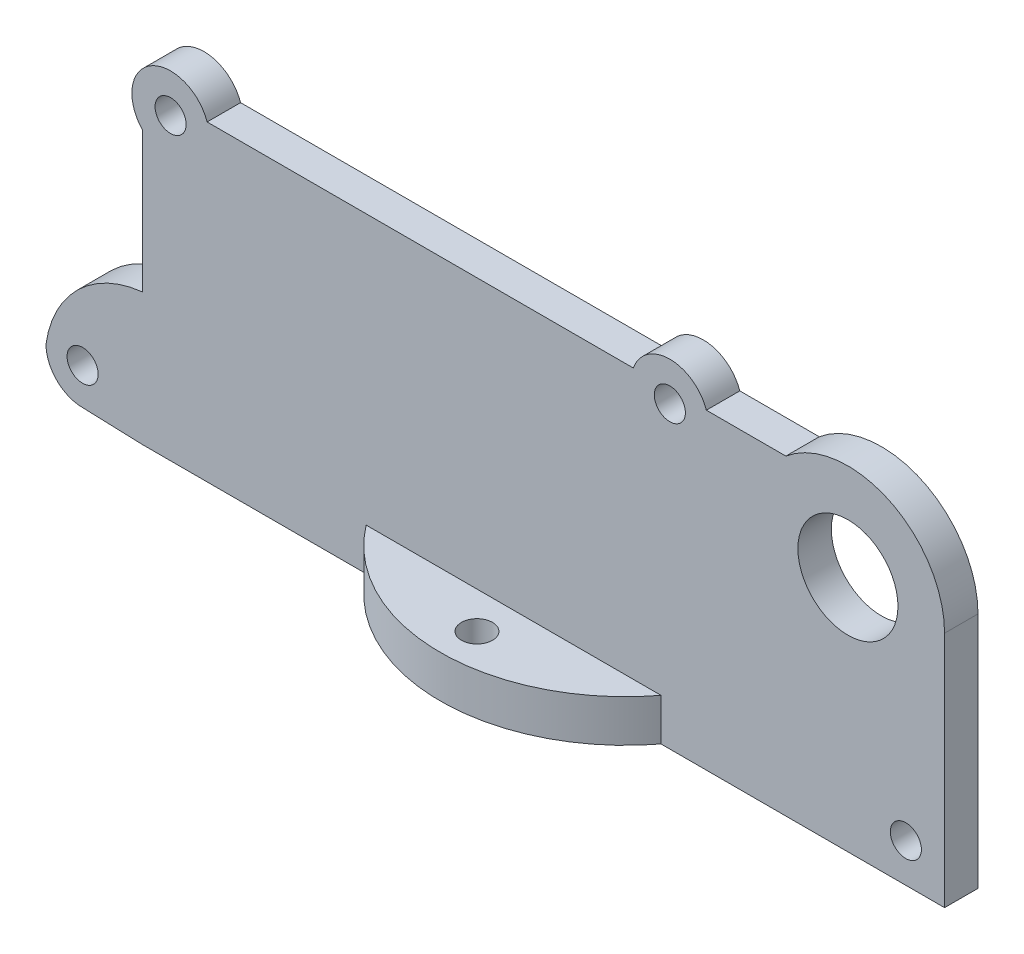
SolidWorks part; units mm, degrees
ref_plane "Front Plane" through (0, 0, 0) normal (0, 0, 1) x (1, 0, 0)
ref_plane "Top Plane" through (0, 0, 0) normal (0, 1, 0) x (1, 0, 0)
ref_plane "Right Plane" through (0, 0, 0) normal (1, 0, 0) x (0, 0, -1)
sketch "Sketch1" plane through (0, 0, 0) normal (0, 0, 1) x (1, 0, 0)
  line L1 (-26.416, -9.8) -> (26.416, -9.8)
  line L2 (-26.416, -9.8) -> (-26.416, 9.8)
  line L3 (-26.416, 9.8) -> (26.416, 9.8)
  line L4 (26.416, -9.8) -> (26.416, 9.8)
  line L5 (-26.416, -9.8) -> (26.416, 9.8) construction
  line L6 (-26.416, 9.8) -> (26.416, -9.8) construction
  line L7 (-20.15, -9.8) -> (20.15, -9.8)
  line L8 (-20.15, -9.8) -> (-20.15, 9.8)
  line L9 (-20.15, 9.8) -> (20.15, 9.8)
  line L10 (20.15, -9.8) -> (20.15, 9.8)
  line L11 (-20.15, -9.8) -> (20.15, 9.8) construction
  line L12 (-20.15, 9.8) -> (20.15, -9.8) construction
  line L13 (-26.416, 9.8) -> (26.416, 9.8)
  line L14 (-26.416, 9.8) -> (-26.416, 14.8)
  line L15 (-26.416, 14.8) -> (26.416, 14.8)
  line L16 (26.416, 9.8) -> (26.416, 14.8)
  line L17 (26.416, -9.8) -> (-26.416, -9.8)
  line L18 (26.416, -9.8) -> (26.416, -14.8)
  line L19 (26.416, -14.8) -> (-26.416, -14.8)
  line L20 (-26.416, -9.8) -> (-26.416, -14.8)
  circle A0 centre (-23.95, -4.974) radius 1.675
  circle A1 centre (-23.95, 4.974) radius 1.675
  circle A2 centre (23.95, 4.974) radius 1.675
  circle A3 centre (23.95, -4.974) radius 1.675
  point P0 (0, 0)
  point P14 (0, 0)
  dimension "D1" = 3.35
  dimension "D2" = 3.35
  dimension "D3" = 3.35
  dimension "D4" = 3.35
  dimension "D7" = 4.826
  dimension "D8" = 3.8
  dimension "D9" = 3.8
  dimension "D10" = 4.826
  dimension "D11" = 4.826
  dimension "D12" = 4.826
  dimension "D13" = 3.8
  dimension "D5" = 19.6
  dimension "D6" = 52.832
  dimension "D15" = 40.3
  dimension "D16" = 5
  dimension "D17" = 5
  dimension "3.9" = 3.8
extrude "Boss-Extrude2" add sketch "Sketch1" along normal blind 3.175 contours L1 L8 L3 L2 A1 A0 | L1 L20 L19 L18 | L3 L16 L15 L14 | L10 L1 L4 L3 A3 A2
sketch "Sketch3" plane through (0, 0, 3.175) normal (0, 0, 1) x (1, 0, 0)
  line L0 (26.416, -14.8) -> (56.416, -14.8)
  line L6 (26.416, 14.8) -> (56.416, 14.8)
  line L7 (26.416, 14.8) -> (26.416, -14.906)
  line L8 (26.416, -14.906) -> (56.416, -14.906)
  line L9 (56.416, 14.8) -> (56.416, -14.906)
  line M3 (26.416, -14.8) -> (26.416, 14.8)
  dimension "D2" = 30
extrude "Boss-Extrude3" add sketch "Sketch3" against normal up to surface (3.175 mm away) contours L9 L6 L0 M3 up to face at (0, 0, 0)
sketch "Sketch4" plane through (0, 0, 0) normal (0, 0, -1) x (-1, 0, 0)
  line L3 (-56.416, 14.8) -> (-56.416, -14.8) construction
  line L4 (-56.416, -14.8) -> (26.416, -14.8) construction
  circle A0 centre (-40.576, 7.77) radius 4.75
  dimension "D1" = 15.84
  dimension "D2" = 22.57
  dimension "D3" = 9.5
extrude "Cut-Extrude1" cut sketch "Sketch4" against normal blind 10 contours A0
sketch "Sketch22" plane through (0, 0, 0) normal (0, 0, -1) x (-1, 0, 0)
  line L0 (-52.3294, 14.8) -> (-30.0917, 14.8)
  line L1 (26.416, 14.8) -> (-56.416, 14.8) construction
  circle A0 centre (-40.576, 7.77) radius 9.175
  dimension "D1" = 18.35
extrude "Boss-Extrude14" add sketch "Sketch22" against normal up to surface (3.175 mm away) contours L0 A0
sketch "Sketch23" plane through (0, 0, 0) normal (0, 0, -1) x (-1, 0, 0)
  line L0 (-49.751, 7.77) -> (-49.751, -14.8)
  line L1 (-56.416, -14.8) -> (26.416, -14.8) construction
  circle A0 centre (-40.576, 7.77) radius 9.175
  line M4 (-46.4717, 14.8) -> (-56.416, 14.8)
  line M5 (-56.416, 14.8) -> (-56.416, -14.8)
  line M6 (-56.416, -14.8) -> (26.416, -14.8)
extrude "Cut-Extrude8" cut sketch "Sketch23" against normal blind 10 contours A0 L0 M4 M5 M6
sketch "Sketch24" plane through (0, 0, 0) normal (0, 0, -1) x (-1, 0, 0)
  line L1 (26.416, 14.8) -> (-34.6803, 14.8) construction
  line L2 (26.416, -14.8) -> (26.416, 14.8) construction
  circle A0 centre (23.736, 13.59) radius 1.475
  dimension "D1" = 2.95
  dimension "D2" = 1.21
  dimension "D3" = 2.68
extrude "Cut-Extrude9" cut sketch "Sketch24" against normal blind 10
sketch "Sketch25" plane through (0, 0, 0) normal (0, 0, -1) x (-1, 0, 0)
  circle A0 centre (23.736, 13.59) radius 1.675
  circle A1 centre (23.95, 4.974) radius 1.675
  circle A2 centre (23.95, -4.974) radius 1.675
  circle A7 centre (23.95, -4.974) radius 3.675
  circle A8 centre (23.95, 4.974) radius 3.675
  circle A9 centre (23.736, 13.59) radius 3.675
  dimension "D1" = 2
  dimension "D2" = 2
extrude "Boss-Extrude15" add sketch "Sketch25" against normal up to surface (3.175 mm away) up to face at (5.1596, 5.6407, 3.175)
sketch "Sketch26" plane through (0, 0, 0) normal (0, 0, -1) x (-1, 0, 0)
  line L0 (-49.751, -14.8) -> (26.416, -14.8) construction
  line L2 (-49.751, 7.77) -> (-49.751, -14.8) construction
  circle A0 centre (-46.076, -11.125) radius 1.475
  circle A1 centre (-46.076, -11.125) radius 3.475
  dimension "D1" = 2.95
  dimension "D2" = 3.675
  dimension "D3" = 3.675
  dimension "D4" = 2
extrude "Cut-Extrude12" cut sketch "Sketch26" against normal up to surface (3.175 mm away) contours A0 up to face at (-4.7057, 2.7441, 3.175)
sketch "Sketch27" plane through (0, 0, 0) normal (0, 0, -1) x (-1, 0, 0)
  line L0 (18.6003, 14.8) -> (34.0912, 14.8)
  line L1 (20.2659, 14.8) -> (-34.6803, 14.8) construction
  line L2 (26.416, -11.2494) -> (26.416, 23.8755)
  line L3 (26.416, -14.8) -> (26.416, -7.6988) construction
  line L5 (-26.3458, -14.8) -> (26.3458, -14.8)
  line L6 (-26.3458, -14.8) -> (-26.3458, 14.8)
  line L7 (-26.3458, 14.8) -> (26.3458, 14.8)
  line L8 (26.3458, -14.8) -> (26.3458, 14.8)
  line L9 (-26.3458, -14.8) -> (26.3458, 14.8) construction
  line L10 (-26.3458, 14.8) -> (26.3458, -14.8) construction
  circle A0 centre (-23.6658, 13.59) radius 1.475
  point P8 (0, 0)
  dimension "D1" = 2.68
  dimension "D2" = 1.21
  dimension "D3" = 2.95
extrude "Cut-Extrude13" cut sketch "Sketch27" against normal blind 10 contours L7 A0
sketch "Sketch28" plane through (0, 0, 0) normal (0, 0, -1) x (-1, 0, 0)
  circle A0 centre (-23.6658, 13.59) radius 1.675
  circle A1 centre (-23.6658, 13.59) radius 3.675
  dimension "D1" = 2
extrude "Boss-Extrude16" add sketch "Sketch28" against normal up to surface (3.175 mm away) contours A1 | A0 up to face at (0.0228, 4.5297, 3.175)
sketch "Sketch29" plane through (0, 0, 0) normal (0, 0, -1) x (-1, 0, 0)
  line L0 (26.416, -14.8) -> (28.416, -14.8)
  line L1 (-49.751, -14.8) -> (26.416, -14.8) construction
  line L2 (32.091, -14.6) -> (26.416, -14.8)
  line L3 (26.416, -2.2492) -> (26.416, -14.8)
  circle A0 centre (32.091, -11.125) radius 1.475
  circle A1 centre (32.091, -11.125) radius 3.475
  arc A2 (35.566, -11.125) -> (26.416, -2.2492) centre (25.3024, -12.5515) ccw
  line M7 (26.416, -14.8) -> (26.416, -7.6988)
  arc M8 (26.416, -7.6988) -> (26.416, -2.2492) centre (23.95, -4.974) ccw
  dimension "D2" = 2
  dimension "D3" = 2.95
  dimension "D4" = 3.675
  dimension "D5" = 3.675
  dimension "D1" = 2
extrude "Boss-Extrude17" add sketch "Sketch29" against normal up to surface (3.175 mm away) contours A1 A2 L0 L2 M8 M7 | A1 A2 A0
sketch "Sketch30" plane through (0, 0, 0) normal (0, 0, -1) x (-1, 0, 0)
  line L1 (-26.2988, 10.8128) -> (25.9375, 10.8128)
  line L2 (-26.2988, 10.8128) -> (-26.2988, -10.6791)
  line L3 (-26.2988, -10.6791) -> (25.9375, -10.6791)
  line L4 (25.9375, 10.8128) -> (25.9375, -10.6791)
extrude "Boss-Extrude18" add sketch "Sketch30" against normal up to surface (3.175 mm away) up to face at (-3.2311, 3.2564, 3.175)
sketch "Sketch31" plane through (0, 0, 0) normal (0, 0, -1) x (-1, 0, 0)
  line L0 (26.416, 9.8657) -> (26.416, 0.6861)
  line L1 (26.416, 7.6988) -> (26.416, 11.0754) construction
  line L2 (26.416, 0.6861) -> (31.4744, 3.1631)
  line L3 (31.4744, 3.1631) -> (26.416, 9.8657)
extrude "Cut-Extrude14" cut sketch "Sketch31" against normal blind 10
sketch "Sketch32" plane through (0, -14.8, 0) normal (0, -1, 0) x (-1, 0, 0)
  line L3 (-8.83, -3.175) -> (5.17, -3.175)
  line L5 (-49.751, -3.175) -> (26.416, -3.175) construction
  line L6 (5.17, -3.175) -> (-8.83, -3.175)
  line L7 (-8.83, -3.175) -> (-22.83, -3.175)
  circle A0 centre (-8.83, -6.65) radius 1.475
  circle A1 centre (-8.83, -6.65) radius 3.475
  arc A2 (-8.83, -10.125) -> (5.17, -3.175) centre (-12.3892, 14.6203) ccw
  arc A3 (-8.83, -10.125) -> (-22.83, -3.175) centre (-5.2708, 14.6203) cw
  dimension "D1" = 2.95
  dimension "D3" = 3.475
  dimension "D6" = 25
  dimension "D7" = 25
  dimension "D4" = 14
  dimension "D5" = 14
  dimension "D2" = 2
extrude "Boss-Extrude19" add sketch "Sketch32" against normal blind 4
sketch "Sketch33" plane through (0, 0, 0) normal (0, 0, -1) x (-1, 0, 0)
  circle A0 centre (-23.6658, 13.59) radius 1.475
  circle A1 centre (23.736, 13.59) radius 1.475
  circle A2 centre (-23.6658, 13.59) radius 2.221
  circle A3 centre (23.736, 13.59) radius 2.2147
extrude "Boss-Extrude20" add sketch "Sketch33" against normal up to surface (3.175 mm away) up to face at (3.1571, -1.2543, 3.175)
sketch "Sketch34" plane through (0, -14.8, 0) normal (0, -1, 0) x (-1, 0, 0)
  line L0 (5.17, -3.175) -> (-22.83, -3.175)
  arc A0 (5.17, -3.175) -> (-22.83, -3.175) centre (-8.83, 7.4507) cw
  circle A1 centre (-8.83, -6.65) radius 1.475
  point P9 (0, 0)
extrude "Boss-Extrude21" add sketch "Sketch34" against normal up to surface (4 mm away) contours L0 A0 | A1 up to face at (8.83, -10.8, 6.2398)
